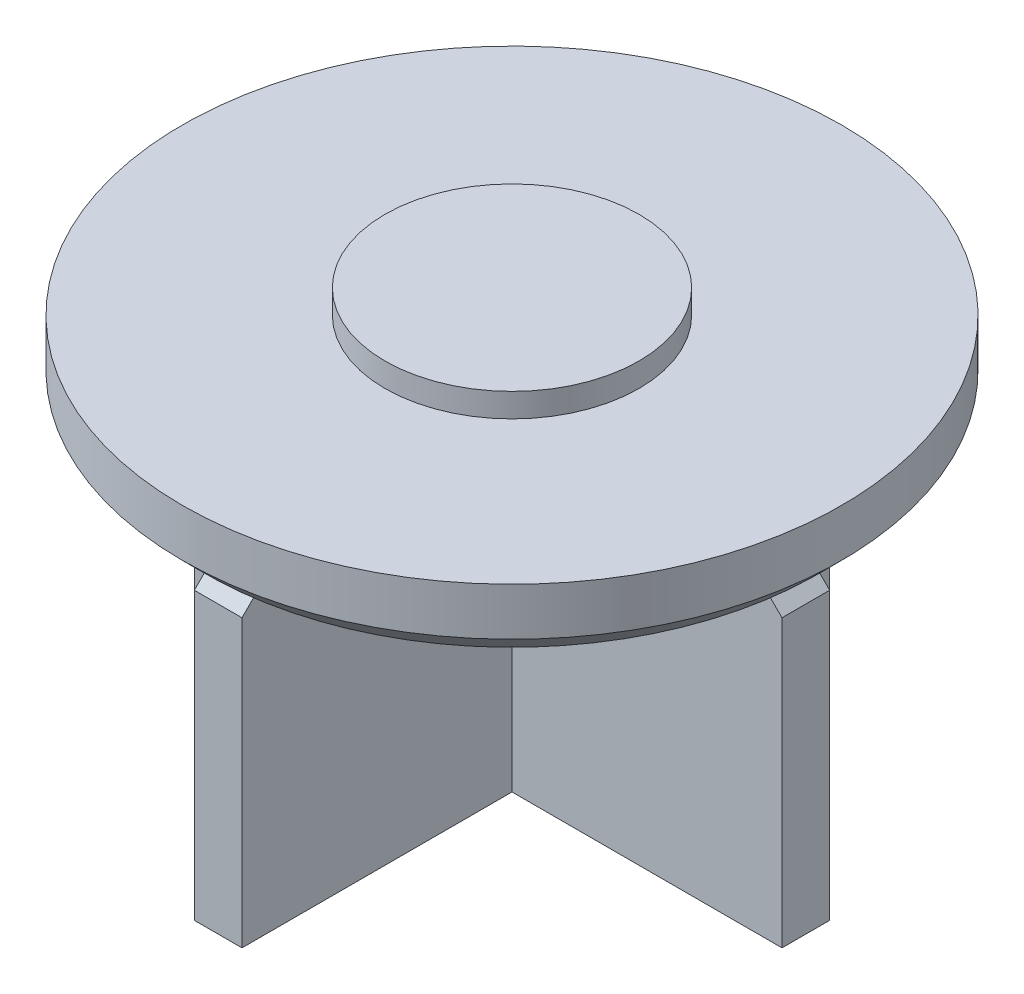
SolidWorks part; units mm, degrees
ref_plane "Piano frontale" through (0, 0, 0) normal (0, 0, 1) x (1, 0, 0)
ref_plane "Piano superiore" through (0, 0, 0) normal (0, 1, 0) x (1, 0, 0)
ref_plane "Piano destro" through (0, 0, 0) normal (1, 0, 0) x (0, 0, -1)
sketch "Schizzo1" plane through (0, 0, 0) normal (0, 0, 1) x (1, 0, 0)
  line L0 (0, 0) -> (-16, 0)
  line L1 (-16, 0) -> (-16, -3)
  line L2 (-16, -3) -> (-41.5, -3)
  line L3 (-41.5, -3) -> (-41.5, -9)
  line L4 (-41.5, -9) -> (-38.5, -12)
  line L5 (-38.5, -12) -> (0, -12)
  line L6 (0, -12) -> (0, 0) construction
  line L7 (0, 0) -> (0, -12)
  dimension "D1" = 32
  dimension "D2" = 83
  dimension "D3" = 6
  dimension "D4" = 45
  dimension "D5" = 3
  dimension "D6" = 3
revolve "Rivoluzione1" add sketch "Schizzo1" angle 360 about L6
sketch "Schizzo2" plane through (0, 0, 0) normal (0, 0, 1) x (1, 0, 0)
  line L0 (0, -12) -> (0, -52)
  line L1 (-38.5, -12) -> (38.5, -12) construction
  line L2 (0, -52) -> (37, -52)
  line L3 (37, -52) -> (37, -16)
  line L4 (37, -16) -> (33, -12)
  line L5 (33, -12) -> (0, -12)
  dimension "D1" = 43
  dimension "D2" = 37
  dimension "D3" = 45
  dimension "D4" = 4
extrude "Estrusione-Estrusione1" add sketch "Schizzo2" along normal mid plane 6
pattern_circular "RipetizioneCircolare1" count 4 over 360 about axis through (0, 0, 0) along (0, 1, 0) of "Estrusione-Estrusione1"
